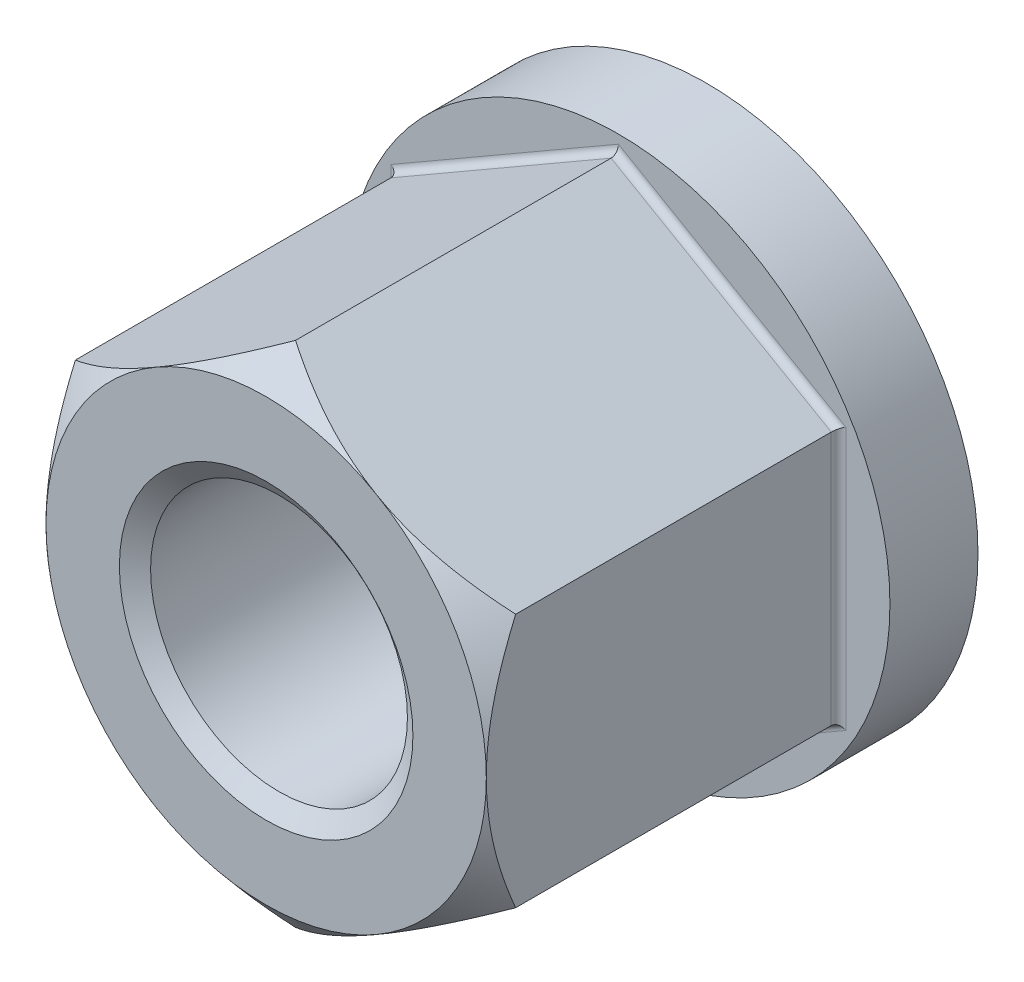
SolidWorks part; units mm, degrees
ref_plane "Plane1" through (0, 0, 0) normal (0, 0, 1) x (1, 0, 0)
ref_plane "Plane2" through (0, 0, 0) normal (0, 1, 0) x (1, 0, 0)
ref_plane "Plane3" through (0, 0, 0) normal (1, 0, 0) x (0, 0, -1)
sketch "BaseNutSke" plane through (0, 0, 0) normal (0, 0, 1) x (1, 0, 0)
  line L6 (15, 8.6603) -> (15, -8.6603)
  line L7 (-15, 8.6603) -> (-15, -8.6603)
  line L8 (15, 8.6603) -> (0, 17.3205)
  line L9 (0, 17.3205) -> (-15, 8.6603)
  line L10 (-15, -8.6603) -> (0, -17.3205)
  line L11 (0, -17.3205) -> (15, -8.6603)
  circle A0 centre (0, 0) radius 8.75
  dimension "Tap_drill" = 17.5
  dimension "Width_flats" = 30
  dimension "D2" = 15
  dimension "D3" = 15
  dimension "D1" = 120
  dimension "D4" = 15
extrude "BaseNut" add sketch "BaseNutSke" against normal blind 30
cosmetic thread "ThreadCosmetic" [suppressed] parameters "Thread_major"=20
sketch "CollarSke" plane through (0, 0, 0) normal (1, 0, 0) x (0, 0, -1)
  line L0 (30, 18.5) -> (24, 18.5)
  line L1 (30, 8.75) -> (30, 18.5)
  line L2 (24, 18.5) -> (24, 8.75)
  line L4 (30, 8.75) -> (24, 8.75)
  line L5 (23.7075, -21.4) -> (19.5103, -21.4) construction
  line L6 (30, 8.6603) -> (30, 17.3205) construction
  line L7 (0, 0) -> (32.9582, 0) construction
  line L8 (30, -8.75) -> (24, -8.75) construction
  line L9 (30, 0) -> (0, 0) construction
  dimension "D1" = 17.5
  dimension "Collar_dia" = 37
  dimension "Collar_thickness" = 6
revolve "Collar" add sketch "CollarSke" angle 360 about L7
sketch "Sketch3" plane through (0, 0, 0) normal (1, 0, 0) x (0, 0, -1)
  line L0 (30, 15) -> (28, 17.3205) construction
  line L1 (28, 17.3205) -> (28, 30.0205) construction
  line L2 (28, 30.0205) -> (42.7, 30.0205) construction
  line L3 (42.7, 30.0205) -> (42.7, 15) construction
  line L4 (42.7, 15) -> (30, 15) construction
  line L5 (30, 8.6603) -> (30, 17.3205) construction
  line L6 (24, 17.3205) -> (0, 17.3205) construction
  line L7 (0, 0) -> (38.6776, 0) construction
  line L8 (30, 0) -> (0, 0) construction
  line L9 (15, 17.3205) -> (15, 44.222) construction
  line L10 (2, 30.0205) -> (-12.7, 30.0205)
  line L11 (-12.7, 30.0205) -> (-12.7, 15)
  line L12 (-12.7, 15) -> (0, 15)
  line L13 (0, 15) -> (2, 17.3205)
  line L14 (2, 17.3205) -> (2, 30.0205)
  line L16 (24, 17.3205) -> (0, 17.3205) construction
  dimension "D1" = 15
  dimension "D2" = 2
  dimension "D4" = 12.7
  dimension "D3" = 12.7
  dimension "D5" = 15
revolve "Chamfer" cut sketch "Sketch3" angle 360 about L7
sketch "Sketch5" plane through (0, 0, 0) normal (1, 0, 0) x (0, 0, -1)
  line L0 (29.9746, 10) -> (29.0118, 8.625)
  line L1 (30.0254, 10) -> (29.9746, 10)
  line L2 (30.0254, 10) -> (30.0254, 8.625)
  line L3 (30.0254, 8.625) -> (29.0118, 8.625)
  line L6 (-0.0508, 10) -> (0, 10)
  line L7 (0, 10) -> (0.9628, 8.625)
  line L9 (0.9628, 8.625) -> (-0.0508, 8.625)
  line L10 (-0.0508, 8.625) -> (-0.0508, 10)
  line L11 (25.0375, 0) -> (38.388, 0) construction
  line L12 (30, 0) -> (0, 0) construction
  dimension "D1" = 35
  dimension "D2" = 0.0508
  dimension "ChamferDepth" = 1.375
  dimension "Offset2" = 30.0762
  dimension "ThreadMajor" = 10
  dimension "Offset1" = 30.0254
revolve "EndChamfer" cut sketch "Sketch5" angle 360 about L11
fillet "Fillet" radius 0.5 6 edges at (-7.5, 12.9904, -24) (7.5, 12.9904, -24) (15, 0, -24) (7.5, -12.9904, -24) (-7.5, -12.9904, -24) (-15, 0, -24)
sketch "ThdSchSke" plane through (0, 0, 0) normal (0, 1, 0) x (1, 0, 0)
  line L0 (-10, 0.0254) -> (-8.75, 0.9007)
  line L1 (-8.75, 0.9007) -> (-4.375, 0.9007)
  line L2 (-4.375, 0.9007) -> (-4.375, -0.8499)
  line L3 (-4.375, -0.8499) -> (-8.75, -0.8499)
  line L4 (-8.75, -0.8499) -> (-10, 0.0254)
  line L5 (-3.175, 2.5) -> (3.175, 2.5) construction
  line L6 (0, 2.5) -> (0, -2.9874) construction
  line L7 (0, 29.0993) -> (0, 0.8753) construction
  dimension "VeeAngle" = 70
  dimension "SideAngle" = 55
  dimension "OverCut" = 8.75
  dimension "Tap_Drill" = 17.5
  dimension "Thread_major" = 20
  dimension "Advance" = 2.5
  dimension "D1" = 0.0254
revolve "ThreadSchematic" [suppressed] cut sketch "ThdSchSke" angle 360 about L6
pattern_linear "ThdSchPat" [suppressed]
equation "\"D2@BaseNutSke\" = \"Width_flats@BaseNutSke\" / 2"
equation "\"D3@BaseNutSke\" = \"Width_flats@BaseNutSke\" / 2"
equation "\"D1@Sketch3\" = \"Width_flats@BaseNutSke\" /2"
equation "\"D2@Sketch3\" = \"Thread_major@ThdSchSke\" *.1"
equation "\"D4@BaseNutSke\" = \"D3@BaseNutSke\""
equation "\"Tap_Drill@ThdSchSke\" = \"Tap_drill@BaseNutSke\""
equation "\"OverCut@ThdSchSke\" = \"Tap_Drill@ThdSchSke\" * 0.5"
equation "\"Num_threads@ThdSchPat\" = int(  ( \"Thickness@BaseNut\" - 0.0508 ) / \"Advance@ThdSchSke\" + 0.999 )  + 1"
equation "\"Advance@ThdSchPat\" = ( \"Thickness@BaseNut\" - 0.0508 ) /  (\"Num_threads@ThdSchPat\" - 1) 'relax it"
equation "' \"Num_threads@ThdSchPat\" = \"Num_threads@ThdSchPat\" - sgn( \"Num_threads@ThdSchPat\" - 1) '---chamfered tips only---"
equation "\"ThreadMajor@Sketch5\" = \"Thread_major@ThdSchSke\" * 0.5"
equation "\"ChamferDepth@Sketch5\" = (\"Thread_major@ThdSchSke\" - \"Tap_drill@BaseNutSke\") * 0.55"
equation "\"Offset1@Sketch5\" = \"Thickness@BaseNut\" + 0.0254"
equation "\"Offset2@Sketch5\" = \"Offset1@Sketch5\" + 0.0508"
equation "\"D1@CollarSke\" = \"Tap_drill@BaseNutSke\""
equation "\"D5@Sketch3\" = \"Thickness@BaseNut\" / 2"
